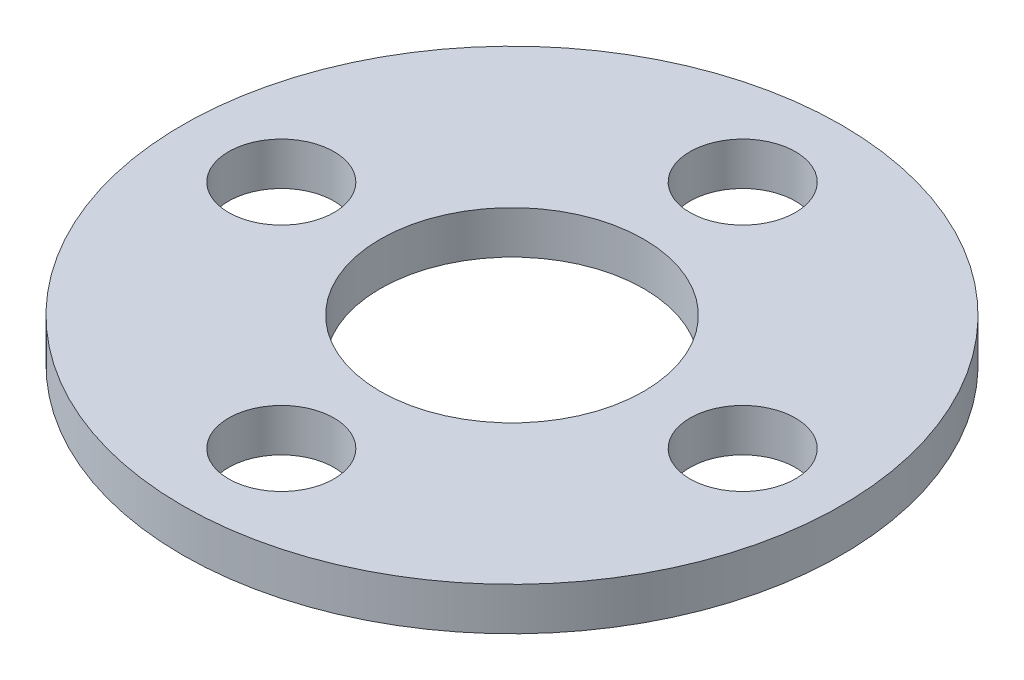
SolidWorks part; units mm, degrees
ref_plane "前视基准面" through (0, 0, 0) normal (0, 0, 1) x (1, 0, 0)
ref_plane "上视基准面" through (0, 0, 0) normal (0, 1, 0) x (1, 0, 0)
ref_plane "右视基准面" through (0, 0, 0) normal (1, 0, 0) x (0, 0, -1)
other "Configuration Table"
sketch "草图1" plane through (0, 0, 0) normal (0, 1, 0) x (1, 0, 0)
  circle A0 centre (0, 0) radius 10
  circle A1 centre (0, 0) radius 4
  circle A2 centre (-7, 0) radius 1.6
  circle A3 centre (0, 7) radius 1.6
  circle A4 centre (7, 0) radius 1.6
  circle A5 centre (0, -7) radius 1.6
  point P15 (0, 0)
  dimension "D1" = 20
  dimension "D2" = 8
  dimension "D5" = 3.2
  dimension "D3" = 7
  dimension "D4" = 4
extrude "凸台-拉伸1" add sketch "草图1" along normal blind 1.3
